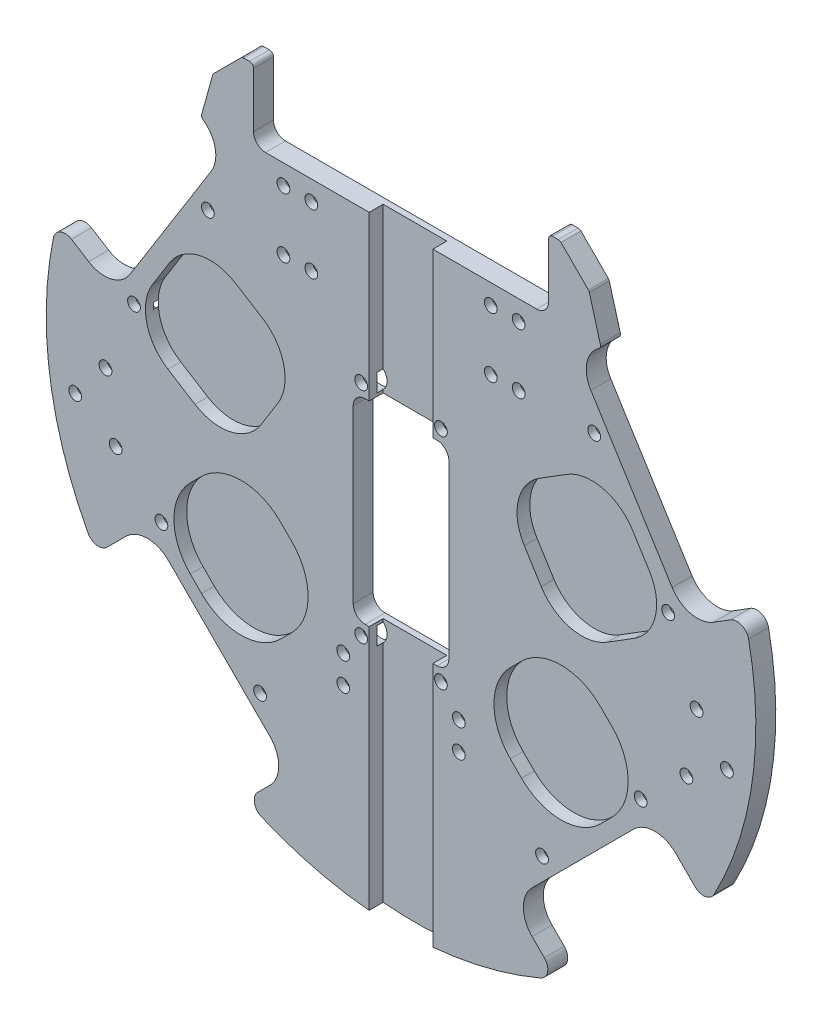
SolidWorks part; units mm, degrees
material "7075-T6，板材(SS)"
ref_plane "前视基准面" through (0, 0, 0) normal (0, 0, 1) x (1, 0, 0)
ref_plane "上视基准面" through (0, 0, 0) normal (0, 1, 0) x (1, 0, 0)
ref_plane "右视基准面" through (0, 0, 0) normal (1, 0, 0) x (0, 0, -1)
sketch "草图1" plane through (0, 0, 0) normal (0, 0, 1) x (1, 0, 0)
  line L0 (-89, 0) -> (89, 0) construction
  line L1 (0, -89) -> (0, 89) construction
  line L2 (0, 0) -> (75.4763, 47.1628) construction
  line L3 (0, 0) -> (62.9325, -62.9325) construction
  line L4 (0, 0) -> (-75.4763, 47.1628) construction
  line L5 (0, 0) -> (-62.9325, -62.9325) construction
  line L6 (-54.2751, 33.9148) -> (-48.446, 43.2434) construction
  line L7 (-54.2751, 33.9148) -> (-66.9931, 13.5617) construction
  line L8 (-45.2548, -45.2548) -> (-35.3553, -55.1543) construction
  line L9 (-45.2548, -45.2548) -> (-60.1041, -30.4056) construction
  line L10 (-57.6673, 36.0345) -> (-71.9751, 13.1372)
  line L11 (-54.2751, 33.9148) -> (-57.6673, 36.0345) construction
  line L12 (-71.9751, 13.1372) -> (-86.2271, 22.0429)
  line L13 (-57.6673, 36.0345) -> (-47.5988, 52.1474)
  line L14 (-45.2548, -45.2548) -> (-48.0833, -48.0833) construction
  line L15 (-48.0833, -48.0833) -> (-27.5772, -68.5894)
  line L16 (-48.0833, -48.0833) -> (-63.6396, -32.5269)
  line L17 (-27.5772, -68.5894) -> (-38.9918, -80.004)
  line L18 (-63.6396, -32.5269) -> (-76.5359, -45.4232)
  line L19 (0, 0) -> (0, 80.4798) construction
  line L20 (34, 62) -> (-34, 62) construction
  line L21 (-34, 62) -> (-34, 80) construction
  line L22 (-34, 80) -> (-41, 80) construction
  line L23 (-50.1909, 62.6065) -> (-39.4371, 80.7898) construction
  line L24 (-47.5988, 52.1474) -> (-53.9592, 56.1218) construction
  line L25 (34, 62) -> (34, 80) construction
  line L26 (34, 80) -> (41, 80) construction
  line L27 (30.8456, 64.7898) -> (30.8456, 80.7898) construction
  line L28 (57.6673, 36.0345) -> (47.5988, 52.1474)
  line L29 (57.6673, 36.0345) -> (71.9751, 13.1372)
  line L30 (71.9751, 13.1372) -> (86.2271, 22.0429)
  line L31 (63.6396, -32.5269) -> (76.5359, -45.4232)
  line L32 (48.0833, -48.0833) -> (63.6396, -32.5269)
  line L33 (48.0833, -48.0833) -> (27.5772, -68.5894)
  line L34 (27.5772, -68.5894) -> (38.9918, -80.004)
  line L35 (0, 80.4798) -> (38, 80.4798) construction
  line L36 (38, 80.4798) -> (38, 70.2696) construction
  line L37 (38, 70.2696) -> (30.8456, 70.2696) construction
  line L38 (30.8456, 70.2696) -> (30.8456, 61.9453) construction
  line L39 (30.8456, 61.9453) -> (32.8892, 61.9453) construction
  line L40 (32.8892, 61.9453) -> (32.8892, 68.4798) construction
  line L41 (32.8892, 68.4798) -> (21, 68.4798) construction
  line L42 (21, 68.4798) -> (21, 62) construction
  line L43 (21, 62) -> (-21, 62) construction
  line L44 (38, 70.2696) -> (38, 65.2696) construction
  line L45 (38, 65.2696) -> (48.6159, 65.2696) construction
  line L46 (48.6159, 65.2696) -> (50.1909, 62.6065) construction
  line L47 (-21, 68.4798) -> (-21, 62) construction
  line L48 (-32.8892, 68.4798) -> (-21, 68.4798) construction
  line L49 (-32.8892, 61.9453) -> (-32.8892, 68.4798) construction
  line L50 (-30.8456, 61.9453) -> (-32.8892, 61.9453) construction
  line L51 (-30.8456, 70.2696) -> (-30.8456, 61.9453) construction
  line L52 (-38, 70.2696) -> (-30.8456, 70.2696) construction
  line L53 (-38, 70.2696) -> (-38, 65.2696) construction
  line L54 (-38, 65.2696) -> (-48.6159, 65.2696) construction
  line L55 (-48.6159, 65.2696) -> (-50.1909, 62.6065) construction
  line L56 (0, 62) -> (0, 63) construction
  line L57 (-37, 63) -> (37, 63)
  line L58 (-30.8456, 80.7898) -> (-39.4371, 80.7898) construction
  line L59 (-30.8456, 64.7898) -> (-30.8456, 80.7898) construction
  line L60 (50.1909, 62.6065) -> (39.4371, 80.7898) construction
  line L61 (30.8456, 80.7898) -> (39.4371, 80.7898) construction
  line L63 (-37, 63) -> (-37, 80.7898)
  line L64 (-37, 80.7898) -> (-39.8456, 80.7898)
  line L65 (-39.8456, 80.7898) -> (-47.1609, 73.4745)
  line L66 (-47.1609, 73.4745) -> (-50.1909, 62.6065)
  line L67 (47.1609, 73.4745) -> (50.1909, 62.6065)
  line L68 (39.8456, 80.7898) -> (47.1609, 73.4745)
  line L69 (37, 80.7898) -> (39.8456, 80.7898)
  line L70 (37, 63) -> (37, 80.7898)
  arc A0 (-86.2271, 22.0429) -> (-76.5359, -45.4232) centre (0, 0) ccw
  circle A1 centre (0, 0) radius 64 construction
  circle A2 centre (0, 0) radius 90 construction
  arc A3 (-47.5988, 52.1474) -> (-50.1909, 62.6065) centre (-53.9592, 56.1218) ccw
  arc A4 (-38.9918, -80.004) -> (38.9918, -80.004) centre (0, 0) ccw
  arc A5 (47.5988, 52.1474) -> (50.1909, 62.6065) centre (53.9592, 56.1218) cw
  arc A6 (86.2271, 22.0429) -> (76.5359, -45.4232) centre (0, 0) cw
  circle A7 centre (0, 0) radius 89 construction
  circle A8 centre (0, 0) radius 68 construction
  point P40 (34, 71)
  point P48 (79.6668, 14.8187)
  point P51 (70.0877, -38.975)
  point P55 (33.2845, -74.2967)
  point P64 (0, 62)
  point P88 (-79.1011, 17.59)
  dimension "D1" = 178
  dimension "D6" = 24
  dimension "D10" = 128
  dimension "D11" = 74
  dimension "D18" = 178
  dimension "D19" = 89
  dimension "D20" = 89
  dimension "D2" = 32
  dimension "D3" = 45
  dimension "D4" = 32
  dimension "D5" = 45
  dimension "D7" = 11
  dimension "D8" = 22
  dimension "D9" = 29
  dimension "D12" = 27
  dimension "D13" = 19
  dimension "D14" = 27
  dimension "D15" = 19
  dimension "D16" = 22
  dimension "D17" = 29
extrude "凸台-拉伸1" add sketch "草图1" along normal blind 5
sketch "草图5" plane through (0, 0, 0) normal (0, 0, -1) x (-1, 0, 0)
  line L0 (0, 0) -> (0, 25) construction
  line L1 (0, -89) -> (0, 89) construction
  line L2 (0, 25) -> (-10, 25) construction
  line L3 (-10, 25) -> (-10, -30) construction
  line L4 (0, 0) -> (0, 43) construction
  line L5 (0, 43) -> (-22.5, 43) construction
  line L6 (-22.5, 43) -> (-22.5, 58) construction
  line L7 (-22.5, 58) -> (-32.3, 58) construction
  line L8 (-32.3, 58) -> (-32.3, 58.4105) construction
  line L9 (-32.3, 58) -> (-32.3, 47.4105) construction
  line L10 (0, 0) -> (0, -36) construction
  line L11 (0, -36) -> (-14.5, -36) construction
  line L12 (-14.5, -36) -> (-14.5, -43) construction
  line L13 (-14.5, -43) -> (-22, -43) construction
  line L14 (-22, -43) -> (-22, -50.2) construction
  line L15 (0, 0) -> (-54.2751, 33.9148) construction
  line L16 (21, 70.2696) -> (34.4228, 70.2696) construction
  line L17 (-22, -72.2) -> (-22, -50.2) construction
  line L18 (0, 0) -> (-75.4763, 47.1628) construction
  line L19 (-54.2751, 33.9148) -> (-48.446, 43.2434) construction
  line L20 (-54.2751, 33.9148) -> (-66.9931, 13.5617) construction
  line L21 (0, 0) -> (-45.2548, -45.2548) construction
  line L22 (0, 0) -> (-62.9325, -62.9325) construction
  line L23 (-45.2548, -45.2548) -> (-35.3553, -55.1543) construction
  line L24 (-45.2548, -45.2548) -> (-60.1041, -30.4056) construction
  line L25 (-81.7399, -13.2015) -> (-72.855, -11.7665) construction
  line L26 (0, 0) -> (-81.7399, -13.2015) construction
  line L27 (-72.855, -11.7665) -> (-74.1305, -3.8689) construction
  line L28 (-72.855, -11.7665) -> (-71.5795, -19.6642) construction
  line L29 (89, 0) -> (-89, 0) construction
  line L30 (38, 70.2696) -> (30.8456, 70.2696) construction
  line L31 (34.4228, 70.2696) -> (35.5, 61.4798) construction
  line L32 (35.5, 61.4798) -> (35.5, 48.4798) construction
  line L33 (0, 0) -> (-89, 0) construction
  circle A0 centre (-10, 25) radius 1.6
  circle A1 centre (-10, -30) radius 1.6
  circle A2 centre (-22.5, 43) radius 1.6
  circle A3 centre (-22.5, 58) radius 1.6
  circle A4 centre (35.5, 61.4798) radius 1.6 construction
  circle A5 centre (35.5, 48.4798) radius 1.6 construction
  circle A6 centre (-14.5, -36) radius 1.6
  circle A7 centre (-14.5, -43) radius 1.6
  circle A8 centre (-35.5, 61.4798) radius 1.6 construction
  circle A9 centre (-35.5, 48.4798) radius 1.6 construction
  arc A10 (-86.2271, 22.0429) -> (-76.5359, -45.4232) centre (0, 0) ccw construction
  circle A11 centre (0, 0) radius 64 construction
  circle A12 centre (29.5, 58) radius 1.6
  circle A13 centre (29.5, 43) radius 1.6
  circle A14 centre (-29.5, 58) radius 1.6
  circle A15 centre (-81.7399, -13.2015) radius 1.6
  circle A16 centre (-74.1305, -3.8689) radius 1.6
  circle A17 centre (-71.5795, -19.6642) radius 1.6
  circle A18 centre (-29.5, 43) radius 1.6
  circle A21 centre (14.5, -43) radius 1.6
  circle A22 centre (14.5, -36) radius 1.6
  circle A24 centre (10, -30) radius 1.6
  circle A25 centre (71.5795, -19.6642) radius 1.6
  circle A26 centre (81.7399, -13.2015) radius 1.6
  circle A27 centre (74.1305, -3.8689) radius 1.6
  circle A28 centre (10, 25) radius 1.6
  circle A31 centre (22.5, 43) radius 1.6
  circle A33 centre (22.5, 58) radius 1.6
  dimension "D1" = 43
  dimension "D4" = 9.174
  dimension "D8" = 32
  dimension "D11" = 3.2
  dimension "D28" = 7
  dimension "D29" = 3.2
  dimension "D33" = 3.2
  dimension "D34" = 3.2
  dimension "D3" = 82.7991
  dimension "D5" = 9
  dimension "D6" = 8
  dimension "D7" = 8
  dimension "D9" = 24
  dimension "D10" = 11
  dimension "D12" = 64
  dimension "D13" = 21
  dimension "D14" = 14
  dimension "D15" = 10.5895
  dimension "D16" = 9.8
  dimension "D17" = 15
  dimension "D18" = 22.5
  dimension "D19" = 10
  dimension "D20" = 25
  dimension "D21" = 55
  dimension "D22" = 36
  dimension "D23" = 14.5
  dimension "D24" = 7
  dimension "D25" = 7.5
  dimension "D26" = 7.2
  dimension "D27" = 22
  dimension "D30" = 7
  dimension "D31" = 7
  dimension "D32" = 7
extrude "切除-拉伸1" cut sketch "草图5" against normal through all
sketch "草图6" plane through (0, 0, 0) normal (0, 0, -1) x (-1, 0, 0)
  line L0 (0, 0) -> (0, -89) construction
  circle A0 centre (-22.5, 58) radius 3
  circle A1 centre (-29.5, 58) radius 3
  circle A2 centre (35.5, 48.4798) radius 3 construction
  circle A3 centre (-22.5, 43) radius 3
  circle A4 centre (-29.5, 43) radius 3
  circle A5 centre (-10, 25) radius 3
  circle A6 centre (29.5, 58) radius 3
  circle A7 centre (-74.1305, -3.8689) radius 3
  circle A8 centre (-81.7399, -13.2015) radius 3
  circle A9 centre (-71.5795, -19.6642) radius 3
  circle A10 centre (29.5, 43) radius 3
  circle A13 centre (-35.5, 48.4798) radius 3 construction
  circle A14 centre (-14.5, -43) radius 3
  circle A15 centre (-10, -30) radius 3
  circle A16 centre (-14.5, -36) radius 3
  circle A18 centre (10, -30) radius 3
  circle A19 centre (14.5, -36) radius 3
  circle A20 centre (14.5, -43) radius 3
  circle A24 centre (74.1305, -3.8689) radius 3
  circle A25 centre (81.7399, -13.2015) radius 3
  circle A26 centre (71.5795, -19.6642) radius 3
  circle A28 centre (10, 25) radius 3
  circle A29 centre (22.5, 43) radius 3
  circle A32 centre (22.5, 58) radius 3
extrude "切除-拉伸2" cut sketch "草图6" against normal blind 3
sketch "草图7" plane through (0, 0, 0) normal (0, 0, -1) x (-1, 0, 0)
  line L0 (0, 0) -> (-12, 0) construction
  line L1 (89, 0) -> (-89, 0) construction
  line L2 (-12, 0) -> (-12, 22) construction
  line L3 (-12, 0) -> (-12, -27) construction
  line L4 (12, -24) -> (12, 19)
  line L6 (-12, 19) -> (-12, -24)
  line L7 (-9, -27) -> (9, -27)
  line L8 (9, 22) -> (-9, 22)
  line L9 (0, 0) -> (0, -27) construction
  line L10 (0, -89) -> (0, 89) construction
  arc A0 (-12, -24) -> (-9, -27) centre (-9, -24) ccw
  arc A1 (12, -24) -> (9, -27) centre (9, -24) cw
  arc A2 (-9, 22) -> (-12, 19) centre (-9, 19) ccw
  arc A3 (9, 22) -> (12, 19) centre (9, 19) cw
extrude "切除-拉伸6" cut sketch "草图7" against normal through all
sketch "草图8" plane through (0, 0, 5) normal (0, 0, 1) x (1, 0, 0)
  line L0 (-8, -94.5354) -> (-8, 65.7524)
  line L1 (-8, 65.7524) -> (8, 65.7524)
  line L3 (-8, -94.5354) -> (8, -94.5354)
  line L5 (8, 65.7524) -> (8, -94.5354)
extrude "切除-拉伸7" cut sketch "草图8" against normal blind 3.5
fillet "圆角1" radius 7.5 6 edges at (-63.6396, -32.5269, 2.5) (71.9751, 13.1372, 2.5) (63.6396, -32.5269, 2.5) (27.5772, -68.5894, 2.5) (-71.9751, 13.1372, 2.5) (-27.5772, -68.5894, 2.5)
fillet "圆角2" radius 3 6 edges at (86.2271, 22.0429, 2.5) (76.5359, -45.4232, 2.5) (38.9918, -80.004, 2.5) (-38.9918, -80.004, 2.5) (-76.5359, -45.4232, 2.5) (-86.2271, 22.0429, 2.5)
sketch "草图9" plane through (0, 0, 5) normal (0, 0, 1) x (1, 0, 0)
  line L0 (0, 0) -> (-40.1385, -28.1052) construction
  line L1 (0, 0) -> (-46.6018, 15.1418) construction
  line L2 (-46.6018, 15.1418) -> (-60.1705, 23.6205) construction
  line L3 (-46.6018, 15.1418) -> (-44.3563, 18.7353) construction
  line L4 (-35.1527, 3.2709) -> (-30.9133, 10.0553)
  line L5 (0, 0) -> (-75.4763, 47.1628) construction
  line L6 (-62.2902, 20.2283) -> (-58.0509, 27.0127)
  line L7 (-62.7659, -28.1052) -> (-17.511, -28.1052) construction
  line L8 (-41.5153, 30.8303) -> (-34.7309, 26.5909)
  line L9 (-40.1385, -28.1052) -> (-51.4522, -39.419) construction
  line L10 (0, 0) -> (-62.9325, -62.9325) construction
  line L11 (-51.4522, -39.419) -> (-50.0379, -40.8332)
  line L12 (-30.239, -40.8332) -> (-27.4105, -38.0047)
  line L13 (-40.1385, -28.1052) -> (-51.4522, -16.7915) construction
  line L14 (-51.4522, -16.7915) -> (-52.8664, -18.2058)
  line L15 (-52.8664, -38.0047) -> (-51.4522, -39.419)
  line L16 (-40.1385, -50.7327) -> (-40.1385, -28.1052) construction
  line L17 (0, 0) -> (0, 49) construction
  line L18 (-58.0509, 27.0127) -> (-47.8743, 20.6537) construction
  line L19 (62.7659, -28.1052) -> (17.511, -28.1052) construction
  line L20 (30.239, -40.8332) -> (40.1385, -30.9337) construction
  line L21 (52.8664, -18.2058) -> (42.9669, -28.1052) construction
  line L22 (-47.8743, 20.6537) -> (-41.5153, 30.8303) construction
  line L23 (40.1385, -50.7327) -> (40.1385, -28.1052) construction
  line L24 (-58.4727, 3.6927) -> (-51.6883, -0.5466)
  line L25 (58.4727, 3.6927) -> (51.6883, -0.5466)
  line L26 (35.1527, 3.2709) -> (30.9133, 10.0553)
  line L27 (41.5153, 30.8303) -> (34.7309, 26.5909)
  line L28 (40.1385, -28.1052) -> (51.4522, -16.7915) construction
  line L29 (-51.4522, -16.7915) -> (-50.0379, -15.3773)
  line L30 (-52.8664, -18.2058) -> (-42.9669, -28.1052) construction
  line L31 (-30.239, -40.8332) -> (-40.1385, -30.9337) construction
  line L32 (-30.239, -15.3773) -> (-27.4105, -18.2058)
  line L33 (40.1385, -28.1052) -> (51.4522, -39.419) construction
  line L34 (0, 0) -> (40.1385, -28.1052) construction
  line L35 (30.239, -15.3773) -> (27.4105, -18.2058)
  line L36 (51.4522, -16.7915) -> (50.0379, -15.3773)
  line L37 (52.8664, -38.0047) -> (51.4522, -39.419)
  line L38 (51.4522, -16.7915) -> (52.8664, -18.2058)
  line L39 (30.239, -40.8332) -> (27.4105, -38.0047)
  line L40 (51.4522, -39.419) -> (50.0379, -40.8332)
  line L41 (0, 0) -> (-89, 0) construction
  line L42 (62.2902, 20.2283) -> (58.0509, 27.0127)
  circle A0 centre (0, 0) radius 49 construction
  arc A1 (-41.5153, 30.8303) -> (-58.0509, 27.0127) centre (-47.8743, 20.6537) ccw
  arc A2 (-34.7309, 26.5909) -> (-30.9133, 10.0553) centre (-41.0899, 16.4143) cw
  arc A3 (-51.6883, -0.5466) -> (-35.1527, 3.2709) centre (-45.3293, 9.63) ccw
  arc A4 (-58.4727, 3.6927) -> (-62.2902, 20.2283) centre (-52.1136, 13.8693) cw
  arc A5 (-30.239, -40.8332) -> (-50.0379, -40.8332) centre (-40.1385, -30.9337) cw
  arc A6 (-52.8664, -38.0047) -> (-52.8664, -18.2058) centre (-42.9669, -28.1052) cw
  arc A7 (-27.4105, -38.0047) -> (-27.4105, -18.2058) centre (-37.31, -28.1052) ccw
  arc A8 (-30.239, -15.3773) -> (-50.0379, -15.3773) centre (-40.1385, -25.2768) ccw
  arc A9 (30.239, -15.3773) -> (50.0379, -15.3773) centre (40.1385, -25.2768) cw
  arc A10 (27.4105, -38.0047) -> (27.4105, -18.2058) centre (37.31, -28.1052) cw
  arc A11 (52.8664, -38.0047) -> (52.8664, -18.2058) centre (42.9669, -28.1052) ccw
  arc A12 (30.239, -40.8332) -> (50.0379, -40.8332) centre (40.1385, -30.9337) ccw
  arc A13 (58.4727, 3.6927) -> (62.2902, 20.2283) centre (52.1136, 13.8693) ccw
  arc A14 (51.6883, -0.5466) -> (35.1527, 3.2709) centre (45.3293, 9.63) cw
  arc A15 (34.7309, 26.5909) -> (30.9133, 10.0553) centre (41.0899, 16.4143) ccw
  arc A16 (41.5153, 30.8303) -> (58.0509, 27.0127) centre (47.8743, 20.6537) cw
  arc A17 (-87.1873, 17.8713) -> (-78.5091, -41.9204) centre (0, 0) ccw construction
  point P29 (-33.033, 6.6631)
  point P35 (-50.5737, 32.3461)
  point P43 (-63.8061, 11.1699)
  point P45 (-55.0805, 1.5731)
  point P57 (40.1385, -11.2768)
  point P65 (55.0805, 1.5731)
  dimension "D1" = 16
  dimension "D2" = 49
  dimension "D3" = 4
  dimension "D5" = 12
extrude "切除-拉伸8" cut sketch "草图9" against normal blind 3.2
sketch "草图11" plane through (0, 0, 0) normal (0, 0, -1) x (-1, 0, 0)
  line L0 (48.446, 43.2434) -> (45.9018, 41.6536) construction
  line L1 (48.446, 43.2434) -> (66.9931, 13.5617) construction
  line L2 (66.9931, 13.5617) -> (64.449, 11.9719) construction
  line L3 (64.449, 11.9719) -> (65.5088, 10.2758) construction
  line L4 (65.5088, 10.2758) -> (72.8478, 14.8617) construction
  line L5 (72.8478, 14.8617) -> (67.908, 23.4178)
  line L6 (67.908, 23.4178) -> (66.1759, 22.4178)
  line L7 (66.1759, 22.4178) -> (49.1586, 49.6512)
  line L8 (49.1586, 49.6512) -> (50.8547, 50.7111)
  line L9 (50.8547, 50.7111) -> (48.765, 54.0553)
  line L10 (48.765, 54.0553) -> (46.2208, 52.4656) construction
  line L11 (46.2208, 52.4656) -> (45.6734, 42.0192) construction
  line L12 (45.6734, 42.0192) -> (64.449, 11.9719) construction
  line L13 (72.8478, 14.8617) -> (77.999, 6.2888)
  line L14 (77.999, 6.2888) -> (66.5678, -0.8543)
  line L15 (66.5678, -0.8543) -> (31.5931, 55.1169)
  line L16 (31.5931, 55.1169) -> (43.4658, 62.5358)
  line L17 (43.4658, 62.5358) -> (48.765, 54.0553)
  line L18 (0, 0) -> (0, 62) construction
  line L19 (-34, 62) -> (34, 62) construction
  line L20 (32.9292, -53.3379) -> (57.9828, -28.2843) construction
  line L21 (-35.3553, -55.1543) -> (-33.234, -53.033) construction
  line L22 (31.1127, -63.6396) -> (32.9292, -53.3379) construction
  line L23 (33.234, -65.7609) -> (31.1127, -63.6396) construction
  line L24 (59.397, -26.8701) -> (65.7609, -33.234) construction
  line L25 (57.9828, -28.2843) -> (59.397, -26.8701) construction
  line L26 (60.1041, -30.4056) -> (57.9828, -28.2843) construction
  line L27 (35.3553, -55.1543) -> (60.1041, -30.4056) construction
  line L28 (35.3553, -55.1543) -> (33.234, -53.033) construction
  line L29 (21.9203, -77.0746) -> (33.234, -65.7609)
  line L30 (12.0208, -67.1751) -> (21.9203, -77.0746)
  line L31 (62.2254, -16.9706) -> (12.0208, -67.1751)
  line L32 (72.1249, -26.8701) -> (62.2254, -16.9706)
  line L33 (65.7609, -33.234) -> (72.1249, -26.8701)
  line L34 (36.0225, -62.9725) -> (33.234, -65.7609)
  line L35 (34.6083, -61.5583) -> (36.0225, -62.9725)
  line L36 (57.3156, -38.8509) -> (34.6083, -61.5583)
  line L37 (58.7298, -40.2651) -> (57.3156, -38.8509)
  line L38 (65.7609, -33.234) -> (58.7298, -40.2651)
  line L39 (-35.3553, -55.1543) -> (-60.1041, -30.4056) construction
  line L40 (-60.1041, -30.4056) -> (-57.9828, -28.2843) construction
  line L41 (-57.9828, -28.2843) -> (-59.397, -26.8701) construction
  line L42 (-59.397, -26.8701) -> (-65.7609, -33.234) construction
  line L43 (-33.234, -65.7609) -> (-31.1127, -63.6396) construction
  line L44 (-31.1127, -63.6396) -> (-32.9292, -53.3379) construction
  line L45 (-32.9292, -53.3379) -> (-57.9828, -28.2843) construction
  line L46 (-45.6734, 42.0192) -> (-64.449, 11.9719) construction
  line L47 (-46.2208, 52.4656) -> (-45.6734, 42.0192) construction
  line L48 (-48.765, 54.0553) -> (-46.2208, 52.4656) construction
  line L49 (-65.5088, 10.2758) -> (-72.8478, 14.8617) construction
  line L50 (-64.449, 11.9719) -> (-65.5088, 10.2758) construction
  line L51 (-66.9931, 13.5617) -> (-64.449, 11.9719) construction
  line L52 (-48.446, 43.2434) -> (-66.9931, 13.5617) construction
  line L53 (-48.446, 43.2434) -> (-45.9018, 41.6536) construction
  line L54 (-65.7609, -33.234) -> (-58.7298, -40.2651)
  line L55 (-58.7298, -40.2651) -> (-57.3156, -38.8509)
  line L56 (-57.3156, -38.8509) -> (-34.6083, -61.5583)
  line L57 (-34.6083, -61.5583) -> (-36.0225, -62.9725)
  line L58 (-36.0225, -62.9725) -> (-33.234, -65.7609)
  line L59 (-65.7609, -33.234) -> (-72.1249, -26.8701)
  line L60 (-72.1249, -26.8701) -> (-62.2254, -16.9706)
  line L61 (-62.2254, -16.9706) -> (-12.0208, -67.1751)
  line L62 (-12.0208, -67.1751) -> (-21.9203, -77.0746)
  line L63 (-21.9203, -77.0746) -> (-33.234, -65.7609)
  line L64 (-43.4658, 62.5358) -> (-48.765, 54.0553)
  line L65 (-31.5931, 55.1169) -> (-43.4658, 62.5358)
  line L66 (-66.5678, -0.8543) -> (-31.5931, 55.1169)
  line L67 (-77.999, 6.2888) -> (-66.5678, -0.8543)
  line L68 (-72.8478, 14.8617) -> (-77.999, 6.2888)
  line L69 (-50.8547, 50.7111) -> (-48.765, 54.0553)
  line L70 (-49.1586, 49.6512) -> (-50.8547, 50.7111)
  line L71 (-66.1759, 22.4178) -> (-49.1586, 49.6512)
  line L72 (-67.908, 23.4178) -> (-66.1759, 22.4178)
  line L73 (-72.8478, 14.8617) -> (-67.908, 23.4178)
  line L74 (0, 0) -> (57.6673, 36.0345) construction
  line L75 (0, 0) -> (89, 0) construction
  arc A1 (78.5091, -41.9204) -> (87.1873, 17.8713) centre (0, 0) ccw construction
  dimension "D1" = 32
sketch "草图15" plane through (0, 0, 5) normal (0, 0, 1) x (1, 0, 0)
  line L0 (0, 0) -> (0, -27) construction
  line L1 (-8, -27) -> (8, -27) construction
  circle A0 centre (-66.9931, 13.5617) radius 1.6
  circle A1 centre (-48.446, 43.2434) radius 1.6
  circle A2 centre (-60.1041, -30.4056) radius 1.6
  circle A3 centre (-35.3553, -55.1543) radius 1.6
  circle A4 centre (35.3553, -55.1543) radius 1.6
  circle A5 centre (60.1041, -30.4056) radius 1.6
  circle A6 centre (66.9931, 13.5617) radius 1.6
  circle A7 centre (48.446, 43.2434) radius 1.6
extrude "切除-拉伸12" cut sketch "草图15" against normal up to next
sketch "草图16" plane through (0, 0, 0) normal (0, 0, -1) x (-1, 0, 0)
  circle A0 centre (-60.1041, -30.4056) radius 3
  circle A1 centre (-35.3553, -55.1543) radius 3
  circle A2 centre (-66.9931, 13.5617) radius 3
  circle A3 centre (-48.446, 43.2434) radius 3
  circle A4 centre (48.446, 43.2434) radius 3
  circle A5 centre (66.9931, 13.5617) radius 3
  circle A6 centre (60.1041, -30.4056) radius 3
  circle A7 centre (35.3553, -55.1543) radius 3
extrude "切除-拉伸13" cut sketch "草图16" against normal blind 3
fillet "圆角4" radius 3 2 edges at (37, 63, 2.5) (-37, 63, 2.5)
fillet "圆角5" radius 1 8 edges at (50.1909, 62.6065, 2.5) (47.1609, 73.4745, 2.5) (39.8456, 80.7898, 2.5) (37, 80.7898, 2.5) (-37, 80.7898, 2.5) (-39.8456, 80.7898, 2.5) (-47.1609, 73.4745, 2.5) (-50.1909, 62.6065, 2.5)
